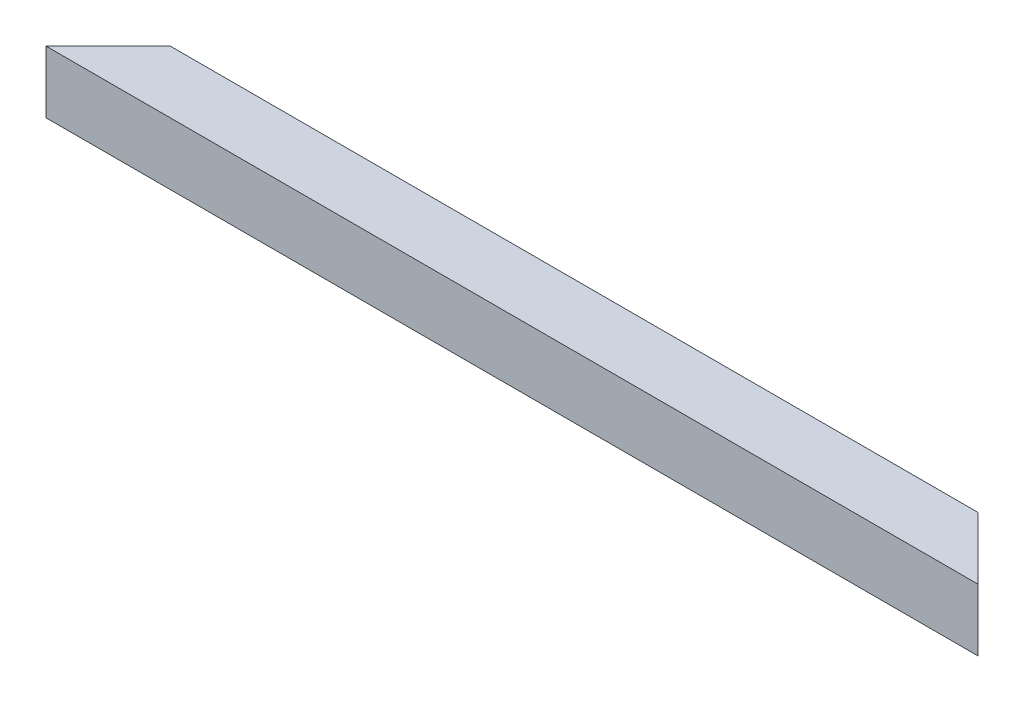
SolidWorks part; units mm, degrees
ref_plane "Front" through (0, 0, 0) normal (0, 0, 1) x (1, 0, 0)
ref_plane "Top" through (0, 0, 0) normal (0, 1, 0) x (1, 0, 0)
ref_plane "Right" through (0, 0, 0) normal (1, 0, 0) x (0, 0, -1)
sketch "Эскиз1" plane through (0, 0, 0) normal (0, 1, 0) x (1, 0, 0)
  line L0 (220.7288, -217.7121) -> (180.7288, -177.7121)
  line L1 (-339.2712, -177.7121) -> (180.7288, -177.7121)
  line L3 (-379.2712, -217.7121) -> (220.7288, -217.7121)
  line L5 (-379.2712, -217.7121) -> (-339.2712, -177.7121)
  dimension "D1" = 600
  dimension "D2" = 40
  dimension "D3" = 45
  dimension "D4" = 45
extrude "Бобышка-Вытянуть1" add sketch "Эскиз1" along normal blind 40
